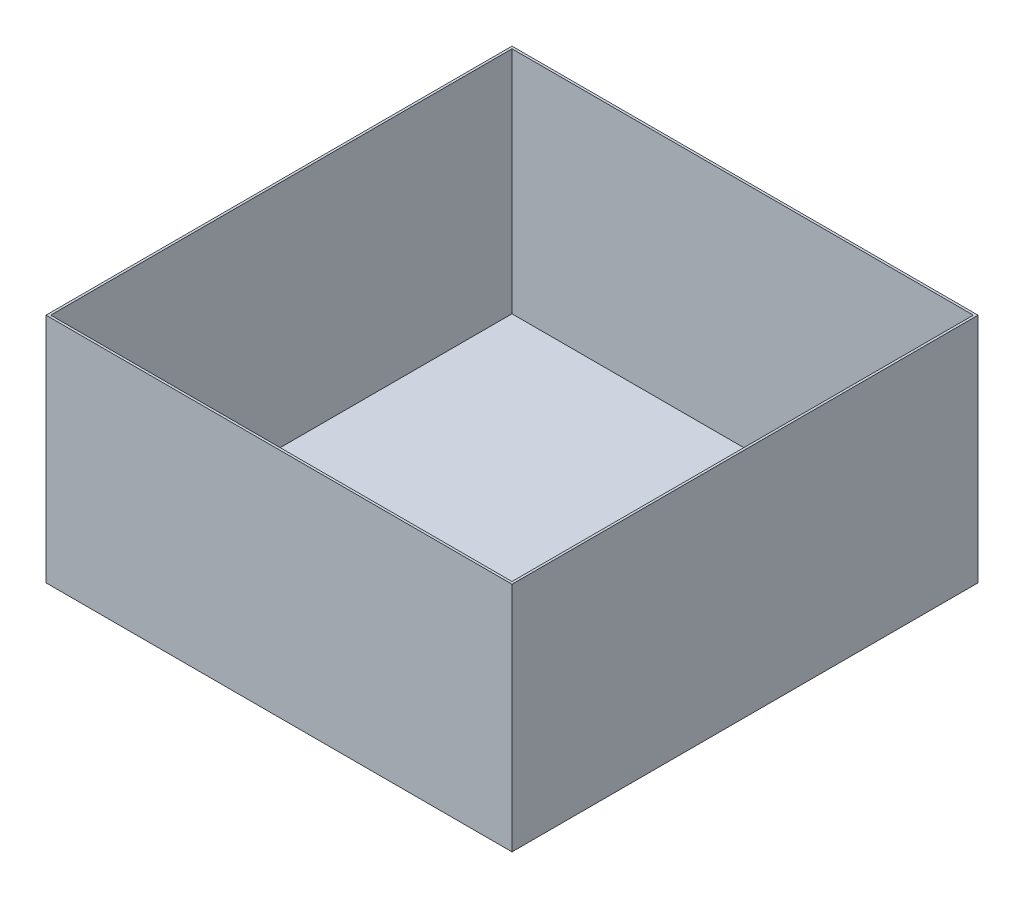
SolidWorks part; units mm, degrees
ref_plane "Alzado" through (0, 0, 0) normal (0, 0, 1) x (1, 0, 0)
ref_plane "Planta" through (0, 0, 0) normal (0, 1, 0) x (1, 0, 0)
ref_plane "Vista lateral" through (0, 0, 0) normal (1, 0, 0) x (0, 0, -1)
sketch "Croquis1" plane through (0, 0, 0) normal (0, 1, 0) x (1, 0, 0)
  line L1 (-41.3831, 24.1133) -> (159.6169, 24.1133)
  line L2 (-41.3831, 24.1133) -> (-41.3831, -176.8867)
  line L3 (-41.3831, -176.8867) -> (159.6169, -176.8867)
  line L4 (159.6169, 24.1133) -> (159.6169, -176.8867)
  dimension "D1" = 201
  dimension "D2" = 201
extrude "Saliente-Extruir1" add sketch "Croquis1" along normal blind 100
shell "Vaciado1" thickness 1
